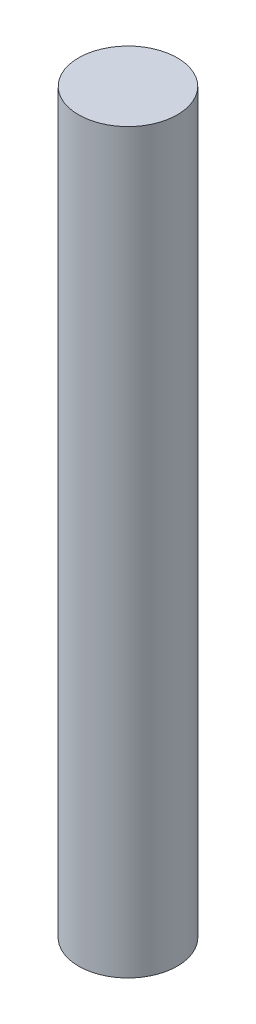
SolidWorks part; units mm, degrees
ref_plane "Plano frontal" through (0, 0, 0) normal (0, 0, 1) x (1, 0, 0)
ref_plane "Plano superior" through (0, 0, 0) normal (0, 1, 0) x (1, 0, 0)
ref_plane "Plano direito" through (0, 0, 0) normal (1, 0, 0) x (0, 0, -1)
sketch "Esboço1" plane through (0, 0, 0) normal (0, 1, 0) x (1, 0, 0)
  circle A0 centre (0, 0) radius 0.595
  dimension "D1" = 1.19
extrude "FingeQueEhUmParafuso" add sketch "Esboço1" along normal blind 8.8872
